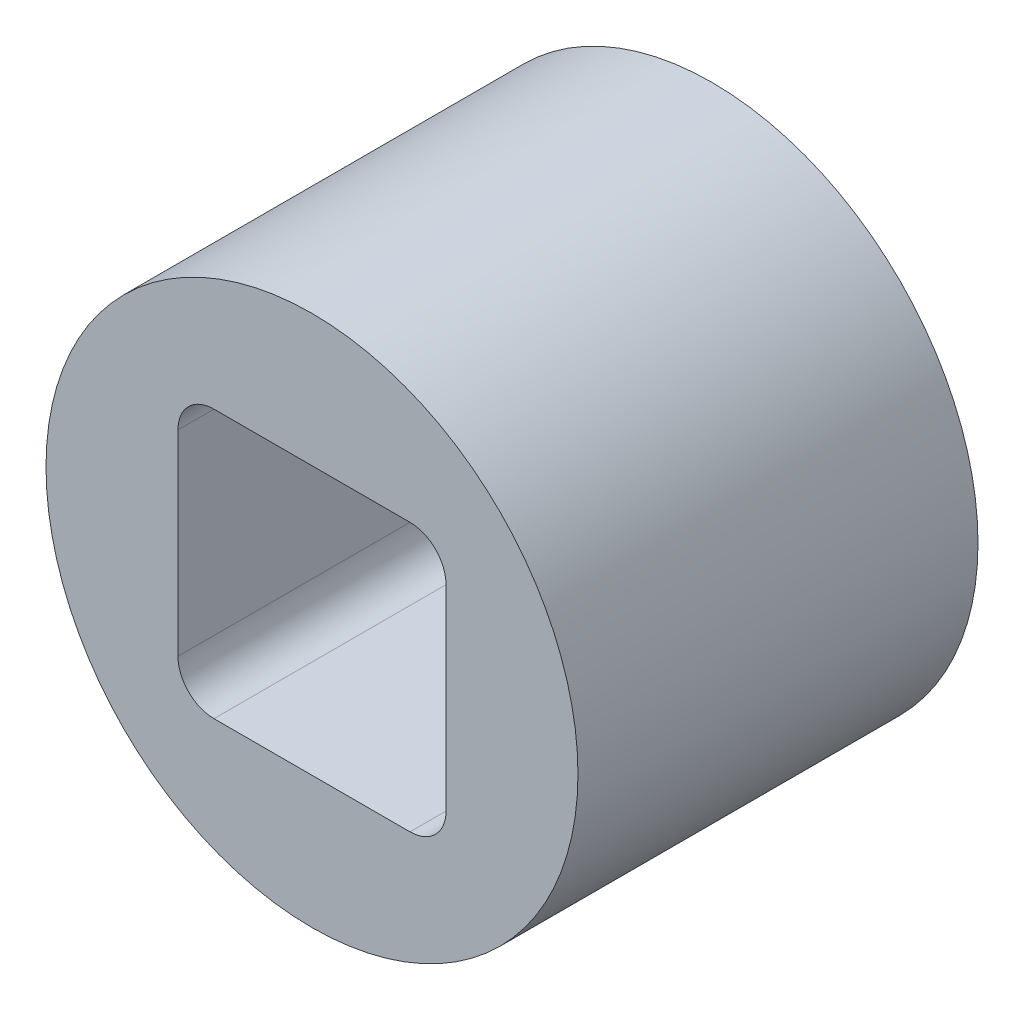
SolidWorks part; units mm, degrees
ref_plane "Front Plane" through (0, 0, 0) normal (0, 0, 1) x (1, 0, 0)
ref_plane "Top Plane" through (0, 0, 0) normal (0, 1, 0) x (1, 0, 0)
ref_plane "Right Plane" through (0, 0, 0) normal (1, 0, 0) x (0, 0, -1)
sketch "Sketch1" plane through (0, 0, 0) normal (0, 0, 1) x (1, 0, 0)
  line L1 (-1.6, -1.6) -> (1.6, -1.6)
  line L2 (-1.6, -1.6) -> (-1.6, 1.6)
  line L3 (-1.6, 1.6) -> (1.6, 1.6)
  line L4 (1.6, -1.6) -> (1.6, 1.6)
  line L5 (-1.6, -1.6) -> (1.6, 1.6) construction
  line L6 (-1.6, 1.6) -> (1.6, -1.6) construction
  circle A0 centre (0, 0) radius 3.175
  dimension "D1" = 6.35
  dimension "D2" = 3.2
  dimension "D3" = 3.2
extrude "Boss-Extrude1" add sketch "Sketch1" along normal blind 4.7752
fillet "Fillet1" radius 0.43 4 edges at (1.6, 1.6, 2.3876) (1.6, -1.6, 2.3876) (-1.6, -1.6, 2.3876) (-1.6, 1.6, 2.3876)
